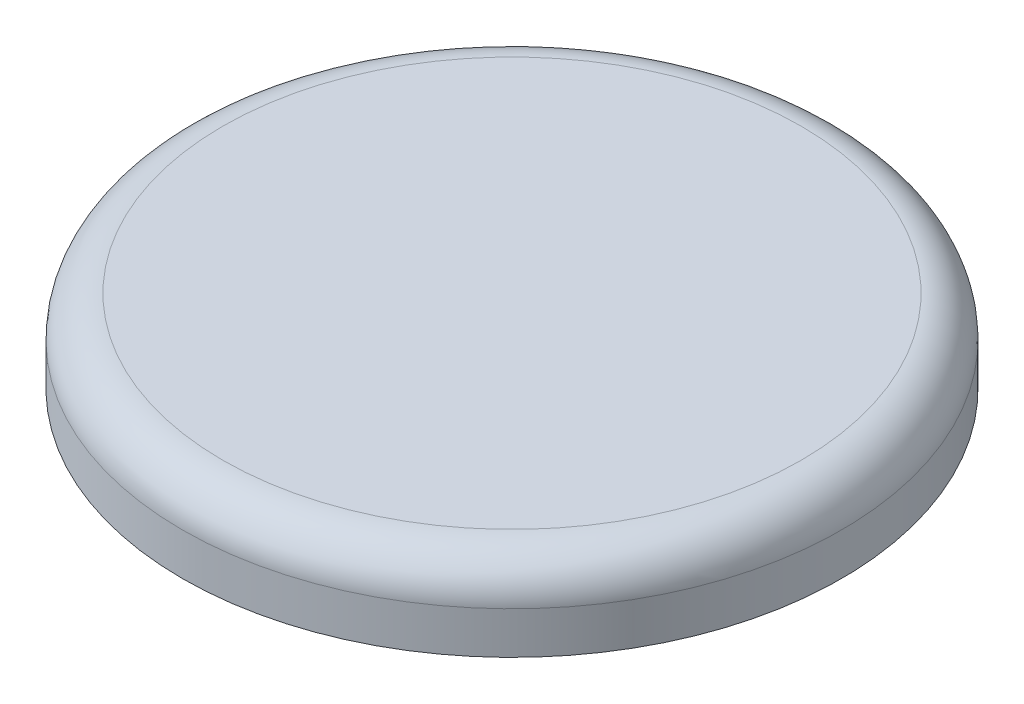
SolidWorks part; units mm, degrees
ref_plane "Front Plane" through (0, 0, 0) normal (0, 0, 1) x (1, 0, 0)
ref_plane "Top Plane" through (0, 0, 0) normal (0, 1, 0) x (1, 0, 0)
ref_plane "Right Plane" through (0, 0, 0) normal (1, 0, 0) x (0, 0, -1)
sketch "Sketch1" plane through (0, 0, 0) normal (0, 0, 1) x (1, 0, 0)
  line L0 (0, 0) -> (-100.33, 0)
  line L1 (-109.22, -8.89) -> (-109.22, -10.795)
  line L2 (-109.22, -10.795) -> (-111.76, -10.795)
  line L3 (-111.76, -10.795) -> (-111.76, -23.495)
  line L4 (-111.76, -23.495) -> (-114.3, -23.495)
  line L5 (-114.3, -23.495) -> (-114.3, -8.89)
  line L6 (0, 0) -> (0, 5.08)
  line L7 (0, 5.08) -> (-100.33, 5.08)
  line L8 (0, 0) -> (0, -23.495) construction
  line L9 (0, -23.495) -> (-111.76, -23.495) construction
  line L10 (-114.3, -23.495) -> (-114.3, -80.645) construction
  arc A0 (-100.33, 0) -> (-109.22, -8.89) centre (-100.33, -8.89) ccw
  arc A1 (-100.33, 5.08) -> (-114.3, -8.89) centre (-100.33, -8.89) ccw
  dimension "D7" = 8.89
  dimension "D1" = 2.54
  dimension "D2" = 5.08
  dimension "D3" = 5.08
  dimension "D5" = 12.7
  dimension "D6" = 28.575
revolve "Revolve1" add sketch "Sketch1" angle 360 about L6
